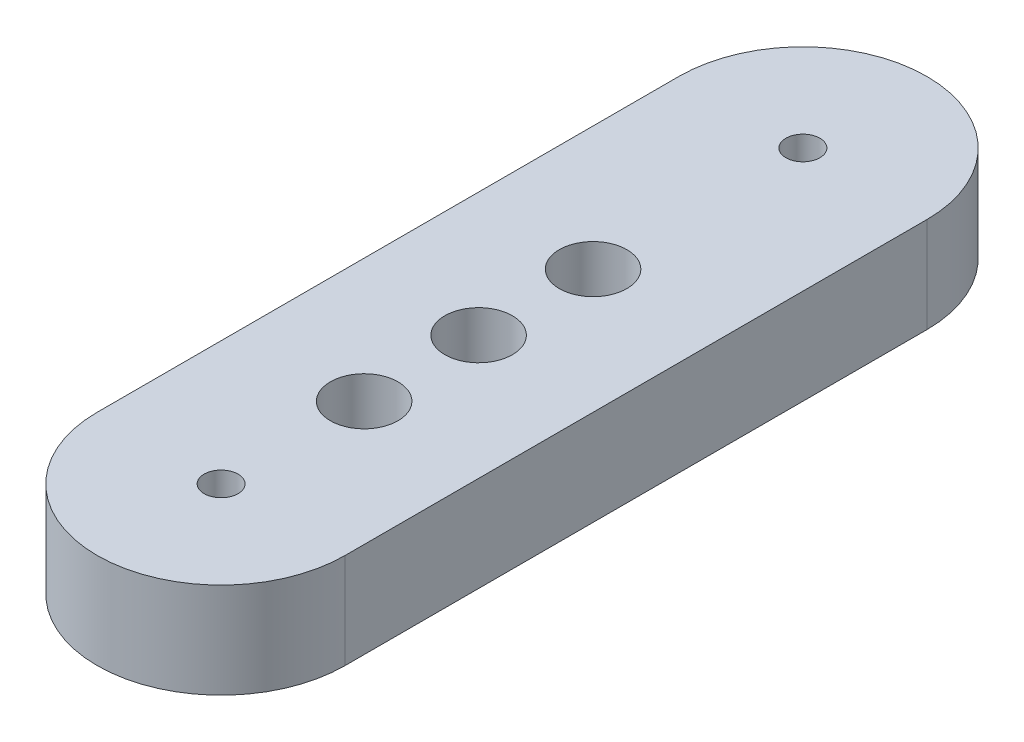
SolidWorks part; units mm, degrees
ref_plane "Front Plane" through (0, 0, 0) normal (0, 0, 1) x (1, 0, 0)
ref_plane "Top Plane" through (0, 0, 0) normal (0, 1, 0) x (1, 0, 0)
ref_plane "Right Plane" through (0, 0, 0) normal (1, 0, 0) x (0, 0, -1)
sketch "Sketch1" plane through (0, 0, 0) normal (0, 1, 0) x (1, 0, 0)
  line L0 (0, -19.3675) -> (0, 19.3675) construction
  line L1 (-8.255, -19.3675) -> (-8.255, 19.3675)
  line L2 (8.255, -19.3675) -> (8.255, 19.3675)
  arc A0 (-8.255, -19.3675) -> (8.255, -19.3675) centre (0, -19.3675) ccw
  arc A1 (8.255, 19.3675) -> (-8.255, 19.3675) centre (0, 19.3675) ccw
  circle A2 centre (0, 19.3675) radius 1.1303
  circle A3 centre (0, -19.3675) radius 1.1303
  circle A4 centre (0, -9.8425) radius 2.25
  circle A5 centre (0, -2.2225) radius 2.25
  circle A6 centre (0, 5.3975) radius 2.25
  point P2 (0, 0)
  dimension "D3" = 2.2606
  dimension "D4" = 4.5
  dimension "D1" = 16.51
  dimension "D2" = 7.62
  dimension "D5" = 9.525
  dimension "D6" = 13.97
  dimension "D7" = 7.62
extrude "Boss-Extrude1" add sketch "Sketch1" along normal blind 6.35
